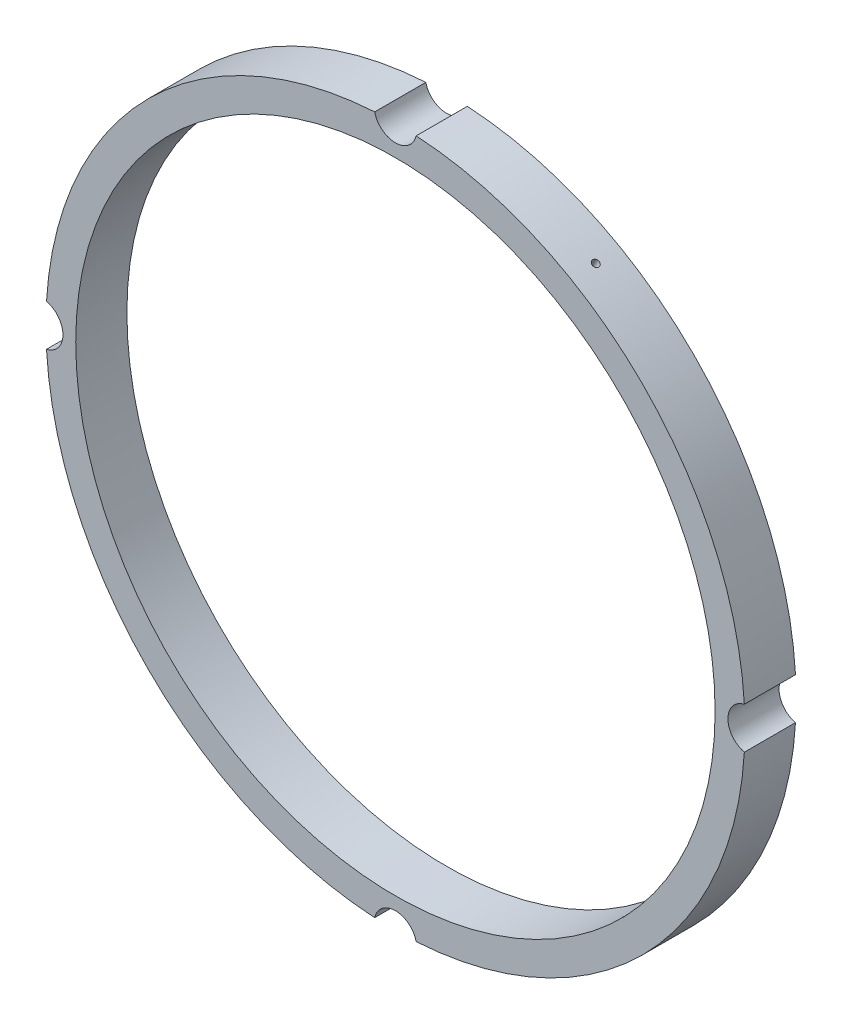
SolidWorks part; units mm, degrees
ref_plane "Front Plane" through (0, 0, 0) normal (0, 0, 1) x (1, 0, 0)
ref_plane "Top Plane" through (0, 0, 0) normal (0, 1, 0) x (1, 0, 0)
ref_plane "Right Plane" through (0, 0, 0) normal (1, 0, 0) x (0, 0, -1)
sketch "Sketch1" plane through (0, 0, 0) normal (0, 0, 1) x (1, 0, 0)
  circle A0 centre (0, 0) radius 75
  circle A1 centre (0, 0) radius 82
extrude "Boss-Extrude1" add sketch "Sketch1" along normal blind 12
sketch "Sketch2" plane through (0, 0, 12) normal (0, 0, 1) x (1, 0, 0)
  circle A0 centre (0, 83) radius 5
extrude "Cut-Extrude1" cut sketch "Sketch2" against normal through all
pattern_circular "CirPattern1" count 4 every 90 about axis through (0, 0, 0) along (0, 0, 1) of "Cut-Extrude1"
hole_wizard "M2x0.4 Tapped Hole1" positions "3DSketch1" profile "Sketch3" tap size "M2x0.4" standard "ANSI Metric"
sketch3d "3DSketch1"
  point P0 (41, 71.0141, 6)
sketch "Sketch3" plane through (41, 71.0141, 6) normal (0, 0, 1) x (-0.866, 0.5, 0)
  line L0 (0, 0) -> (0, 10.4807)
  line L1 (0, 10.4807) -> (0.8, 10)
  line L2 (0.8, 10) -> (0.8, 0)
  line L5 (0.8, 0) -> (0, 0)
  line L10 (0, 10.4807) -> (-0.8, 10) construction
  line L11 (0, -6.35) -> (0, 107.95) construction
  dimension "Tap Drill Dia." = 1.6
  dimension "Tap Drill Depth" = 10
  dimension "Drill Angle" = 118
cosmetic thread "Hole Thread1" parameters "D1"=4, "D2"=2
